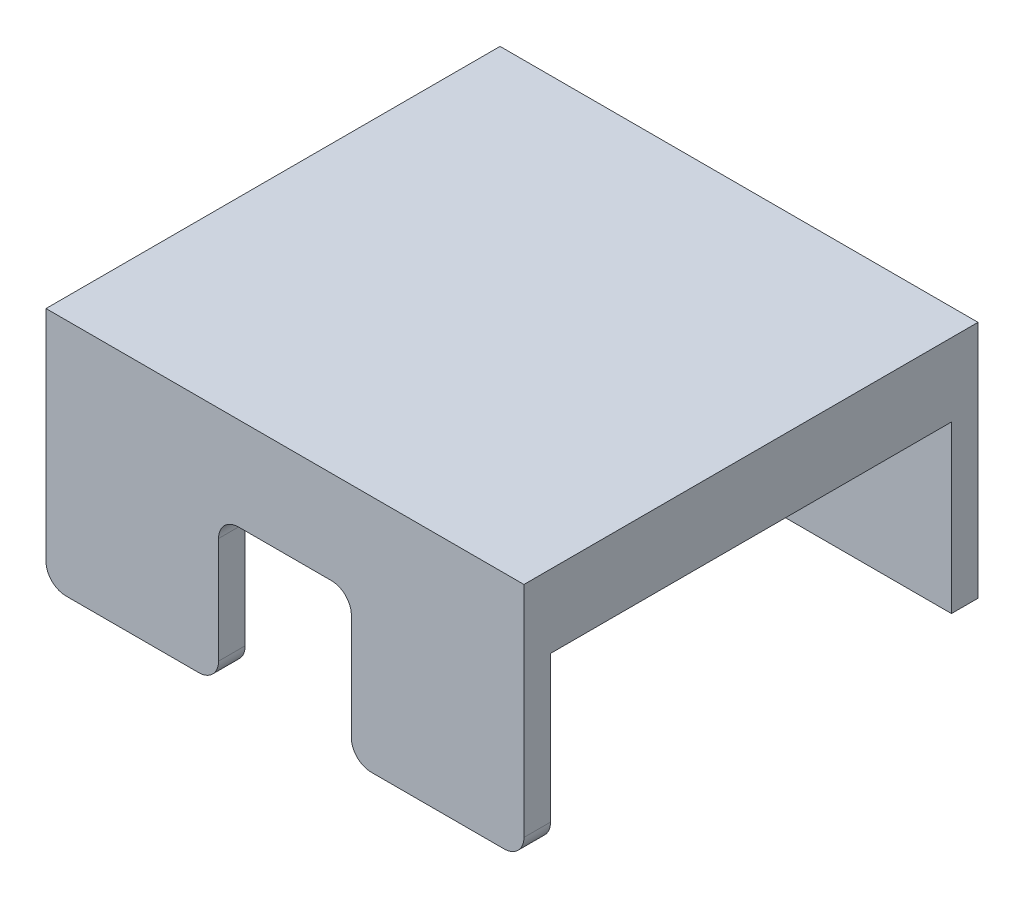
SolidWorks part; units mm, degrees
ref_plane "Front Plane" through (0, 0, 0) normal (0, 0, 1) x (1, 0, 0)
ref_plane "Top Plane" through (0, 0, 0) normal (0, 1, 0) x (1, 0, 0)
ref_plane "Right Plane" through (0, 0, 0) normal (1, 0, 0) x (0, 0, -1)
sketch "Sketch1" plane through (0, 0, 0) normal (0, 1, 0) x (1, 0, 0)
  line L1 (-180, 171) -> (180, 171)
  line L2 (-180, 171) -> (-180, -171)
  line L3 (-180, -171) -> (180, -171)
  line L4 (180, 171) -> (180, -171)
  line L5 (-180, 171) -> (180, -171) construction
  line L6 (-180, -171) -> (180, 171) construction
  point P0 (0, 0)
  dimension "D1" = 342
  dimension "D2" = 360
extrude "Boss-Extrude1" add sketch "Sketch1" along normal blind 55
sketch "Sketch2" plane through (0, 0, 171) normal (0, 0, 1) x (1, 0, 0)
  line L0 (0, 0) -> (0, -50000) construction
  line L1 (-180, 55) -> (-180, -125)
  line L2 (180, 55) -> (50, 55)
  line L3 (180, 55) -> (180, -125)
  line L4 (180, -125) -> (50, -125)
  line L5 (50, -15) -> (50, -125)
  line L6 (50, 55) -> (-50, 55)
  line L8 (50, -15) -> (-50, -15)
  line L9 (0, 55) -> (0, -15)
  line L10 (-180, -125) -> (-50, -125)
  line L11 (-50, -15) -> (-50, -125)
  line L12 (-180, 55) -> (-50, 55)
  line M9 (-180, 0) -> (180, 0)
  dimension "D1" = 180
  dimension "D2" = 130
  dimension "D3" = 70
  dimension "D4" = 50
extrude "Boss-Extrude2" add sketch "Sketch2" against normal blind 20 contours L9 L8 L5 L4 L3 M9 | L11 L8 L9 L1 L10 M9
sketch "Sketch4" plane through (0, 0, 151) normal (0, 0, 1) x (1, 0, 0)
  line L0 (0, 0) -> (0, -50000) construction
  line L1 (180, -125) -> (50, -125) construction
  circle A0 centre (105, -65) radius 4
  circle A1 centre (-105, -65) radius 4
  dimension "D1" = 4
  dimension "D2" = 105
  dimension "D3" = 60
extrude "Cut-Extrude2" cut sketch "Sketch4" along normal blind 10
fillet "Fillet1" radius 15 6 edges at (-50, -15, 161) (50, -15, 161) (-180, -125, 161) (180, -125, 161) (50, -125, 161) (-50, -125, 161)
mirror "Mirror1" about plane through (0, 0, 0) normal (0, 0, 1) of "Boss-Extrude2", "Cut-Extrude2"
